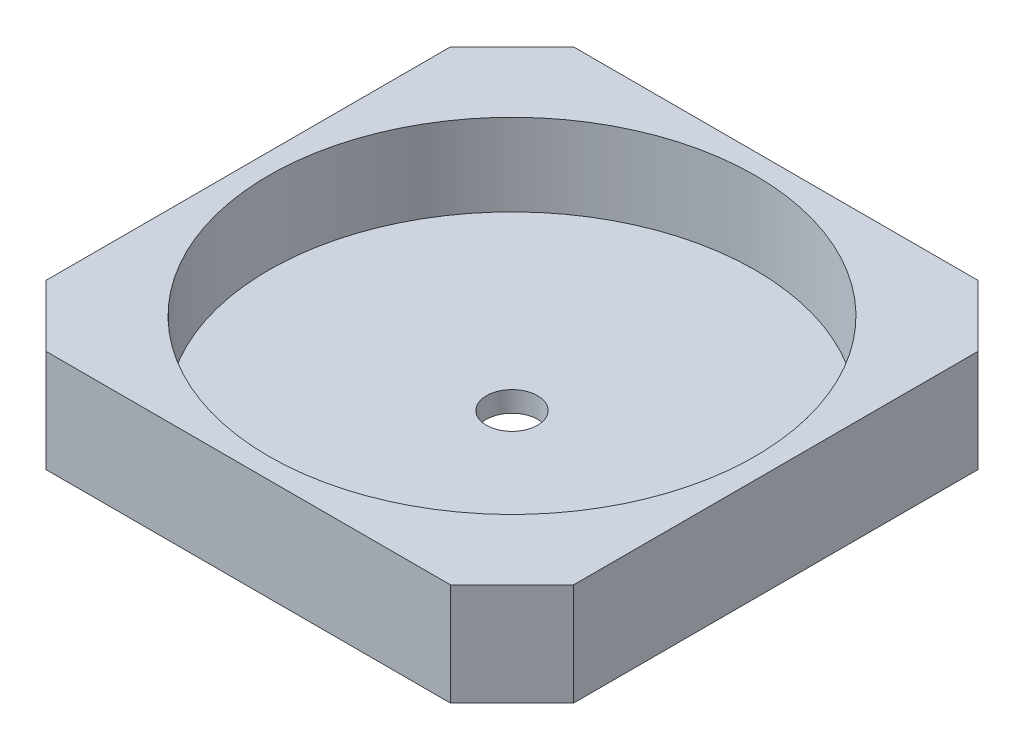
SolidWorks part; units mm, degrees
ref_plane "前基準面" through (0, 0, 0) normal (0, 0, 1) x (1, 0, 0)
ref_plane "上基準面" through (0, 0, 0) normal (0, 1, 0) x (1, 0, 0)
ref_plane "右基準面" through (0, 0, 0) normal (1, 0, 0) x (0, 0, -1)
sketch "草圖1" plane through (0, 0, 0) normal (0, 1, 0) x (1, 0, 0)
  line L0 (-128.75, -98.75) -> (-98.75, -128.75)
  line L1 (-98.75, 128.75) -> (98.75, 128.75)
  line L2 (-128.75, 98.75) -> (-128.75, -98.75)
  line L3 (-98.75, -128.75) -> (98.75, -128.75)
  line L4 (128.75, 98.75) -> (128.75, -98.75)
  line L5 (0, -128.75) -> (0, 128.75) construction
  line L6 (-128.75, 0) -> (128.75, 0) construction
  line L7 (98.75, -128.75) -> (128.75, -98.75)
  line L8 (-128.75, 98.75) -> (-98.75, 128.75)
  line L9 (98.75, 128.75) -> (128.75, 98.75)
  circle A0 centre (0, 0) radius 118.75
  circle A1 centre (0, 0) radius 128.75 construction
  circle A2 centre (0, 0) radius 12.5
  point P5 (128.75, -128.75)
  point P6 (-128.75, 128.75)
  point P7 (-128.75, -128.75)
  point P12 (128.75, 128.75)
  dimension "D1" = 10
  dimension "D2" = 25
  dimension "D3" = 237.5
extrude "填料-伸長1" add sketch "草圖1" along normal blind 50 contours L9 L1 L8 L2 L0 L3 L7 L4 A0
sketch "草圖2" plane through (0, 0, 0) normal (0, -1, 0) x (1, 0, 0)
  line L8 (98.75, -128.75) -> (128.75, -98.75)
  line L9 (128.75, -98.75) -> (128.75, 98.75)
  line L10 (128.75, 98.75) -> (98.75, 128.75)
  line L11 (98.75, 128.75) -> (-98.75, 128.75)
  line L12 (-98.75, 128.75) -> (-128.75, 98.75)
  line L13 (-128.75, 98.75) -> (-128.75, -98.75)
  line L14 (-128.75, -98.75) -> (-98.75, -128.75)
  line L15 (-98.75, -128.75) -> (98.75, -128.75)
  line L16 (98.75, -128.75) -> (128.75, -98.75)
  line L17 (128.75, -98.75) -> (128.75, 98.75)
  line L18 (128.75, 98.75) -> (98.75, 128.75)
  line L19 (98.75, 128.75) -> (-98.75, 128.75)
  line L20 (-98.75, 128.75) -> (-128.75, 98.75)
  line L21 (-128.75, 98.75) -> (-128.75, -98.75)
  line L22 (-128.75, -98.75) -> (-98.75, -128.75)
  line L23 (-98.75, -128.75) -> (98.75, -128.75)
  circle A0 centre (0, 0) radius 12.5
  dimension "D2" = 25
  dimension "D1" = 0
extrude "填料-伸長2" add sketch "草圖2" against normal blind 10
